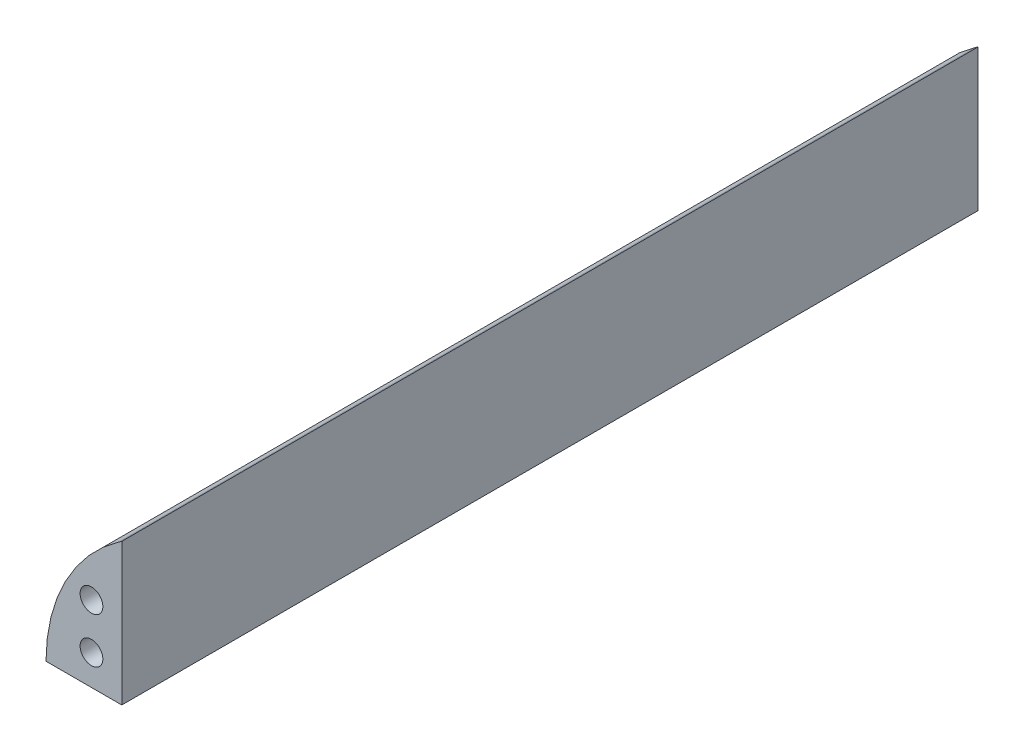
SolidWorks part; units mm, degrees
material "ABS"
ref_plane "Plano frontal" through (0, 0, 0) normal (0, 0, 1) x (1, 0, 0)
ref_plane "Plano superior" through (0, 0, 0) normal (0, 1, 0) x (1, 0, 0)
ref_plane "Plano direito" through (0, 0, 0) normal (1, 0, 0) x (0, 0, -1)
sketch "Esboço1" plane through (0, 0, 0) normal (0, 0, 1) x (1, 0, 0)
  line L0 (11.5, 30.9793) -> (21.5, 30.9793)
  line L1 (21.5, 30.9793) -> (21.5, 49.6876)
  line L2 (21.5, 49.6876) -> (21.1611, 49.4567)
  line L3 (21.1611, 49.4567) -> (19.0663, 47.809)
  line L4 (19.0663, 47.809) -> (17.161, 45.9024)
  line L5 (17.161, 45.9024) -> (15.4865, 43.766)
  line L6 (15.4865, 43.766) -> (14.0749, 41.4312)
  line L7 (14.0749, 41.4312) -> (12.9673, 38.9715)
  line L8 (12.9673, 38.9715) -> (12.156, 36.3727)
  line L9 (12.156, 36.3727) -> (11.6603, 33.6607)
  line L10 (11.6603, 33.6607) -> (11.5, 30.9793)
extrude "Ressalto-extrusão1" add sketch "Esboço1" along normal blind 113 contours L1 L2 L3 L4 L5 L6 L7 L8 L9 L10 L0
sketch "Esboço2" plane through (0, 0, 113) normal (0, 0, 1) x (1, 0, 0)
  line L0 (21.5, 30.9793) -> (21.5, 49.6876) construction
  line L1 (11.5, 30.9793) -> (21.5, 30.9793) construction
  circle A0 centre (17.5, 34.9793) radius 1.5
  circle A1 centre (17.5, 40.9793) radius 1.5
  dimension "D1" = 4
  dimension "D2" = 4
  dimension "D3" = 6
extrude "Corte-extrusão1" cut sketch "Esboço2" against normal blind 113
